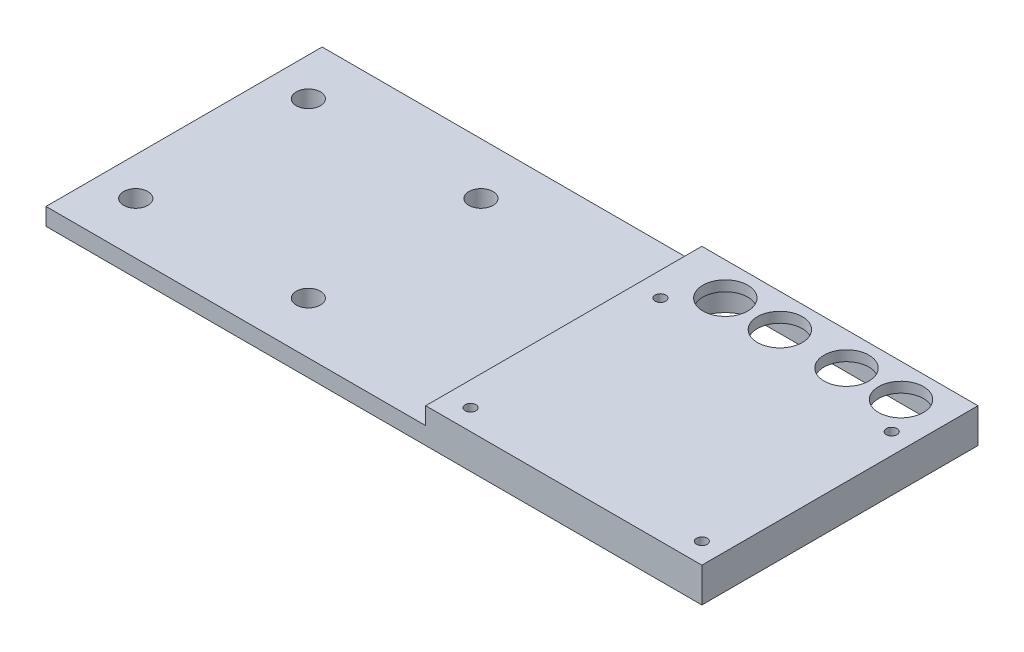
SolidWorks part; units mm, degrees
ref_plane "Front Plane" through (0, 0, 0) normal (0, 0, 1) x (1, 0, 0)
ref_plane "Top Plane" through (0, 0, 0) normal (0, 1, 0) x (1, 0, 0)
ref_plane "Right Plane" through (0, 0, 0) normal (1, 0, 0) x (0, 0, -1)
sketch "Sketch1" plane through (0, 0, 0) normal (0, 1, 0) x (1, 0, 0)
  line L1 (-95, 40) -> (95, 40)
  line L2 (-95, 40) -> (-95, -40)
  line L3 (-95, -40) -> (95, -40)
  line L4 (95, 40) -> (95, -40)
  line L5 (-95, 40) -> (95, -40) construction
  line L6 (-95, -40) -> (95, 40) construction
  point P0 (0, 0)
  dimension "D1" = 80
  dimension "D2" = 190
extrude "Boss-Extrude1" add sketch "Sketch1" along normal blind 5
sketch "Sketch3" plane through (0, 5, 0) normal (0, 1, 0) x (1, 0, 0)
  line L0 (-95, -40) -> (95, -40) construction
  line L1 (95, 40) -> (15, 40)
  line L2 (95, 40) -> (95, -40)
  line L3 (95, -40) -> (15, -40)
  line L4 (15, 40) -> (15, -40)
extrude "Boss-Extrude2" add sketch "Sketch3" along normal blind 5
sketch "Sketch4" plane through (0, 10, 0) normal (0, 1, 0) x (1, 0, 0)
  line L0 (95, -40) -> (95, 40) construction
  line L1 (22, 21) -> (89, 21) construction
  line L2 (22, 21) -> (22, -34) construction
  line L3 (22, -34) -> (89, -34) construction
  line L4 (89, 21) -> (89, -34) construction
  line L5 (15, -40) -> (95, -40) construction
  circle A0 centre (22, 21) radius 1.55
  circle A1 centre (89, 21) radius 1.55
  circle A2 centre (22, -34) radius 1.55
  circle A3 centre (89, -34) radius 1.55
  dimension "D1" = 3.1
  dimension "D2" = 55
  dimension "D3" = 67
  dimension "D4" = 6
  dimension "D5" = 6
extrude "Cut-Extrude1" cut sketch "Sketch4" against normal through all
sketch "Sketch5" plane through (0, 0, 0) normal (0, -1, 0) x (1, 0, 0)
  line L0 (31.4, -30.4) -> (82.3, -30.4) construction
  line L1 (95, 40) -> (95, -40) construction
  line L2 (95, -40) -> (-95, -40) construction
  circle A0 centre (31.4, -30.4) radius 6.5
  circle A1 centre (47.2, -30.4) radius 6.5
  circle A2 centre (66.5, -30.4) radius 6.5
  circle A3 centre (82.3, -30.4) radius 6.5
  dimension "D1" = 13
  dimension "D2" = 15.8
  dimension "D3" = 15.8
  dimension "D4" = 19.3
  dimension "D5" = 12.7
  dimension "D6" = 9.6
extrude "Cut-Extrude2" cut sketch "Sketch5" against normal through all
sketch "Sketch6" plane through (0, 0, 0) normal (0, -1, 0) x (1, 0, 0)
  line L0 (31.4, -21.4) -> (82.3, -21.4)
  line L1 (82.3, -39.4) -> (31.4, -39.4)
  arc A0 (82.3, -21.4) -> (82.3, -39.4) centre (82.3, -30.4) cw
  arc A1 (31.4, -39.4) -> (31.4, -21.4) centre (31.4, -30.4) cw
  circle A2 centre (31.4, -30.4) radius 6.5 construction
  circle A3 centre (82.3, -30.4) radius 6.5 construction
  dimension "D1" = 9
extrude "Cut-Extrude3" cut sketch "Sketch6" against normal offset from surface (7 mm away) 3 up to face at (31.4, 10, -36.9)
sketch "Sketch7" plane through (0, 0, 0) normal (0, -1, 0) x (1, 0, 0)
  line L0 (-84, 0) -> (-95, 0) construction
  line L1 (-84, 25) -> (-34, 25) construction
  line L2 (-84, 25) -> (-84, -25) construction
  line L3 (-84, -25) -> (-34, -25) construction
  line L4 (-34, 25) -> (-34, -25) construction
  line L5 (-95, -40) -> (-95, 40) construction
  circle A0 centre (-84, 25) radius 3.5
  circle A1 centre (-34, 25) radius 3.5
  circle A2 centre (-84, -25) radius 3.5
  circle A3 centre (-34, -25) radius 3.5
  dimension "D1" = 7
  dimension "D2" = 50
  dimension "D3" = 11
extrude "Cut-Extrude4" cut sketch "Sketch7" against normal through all
